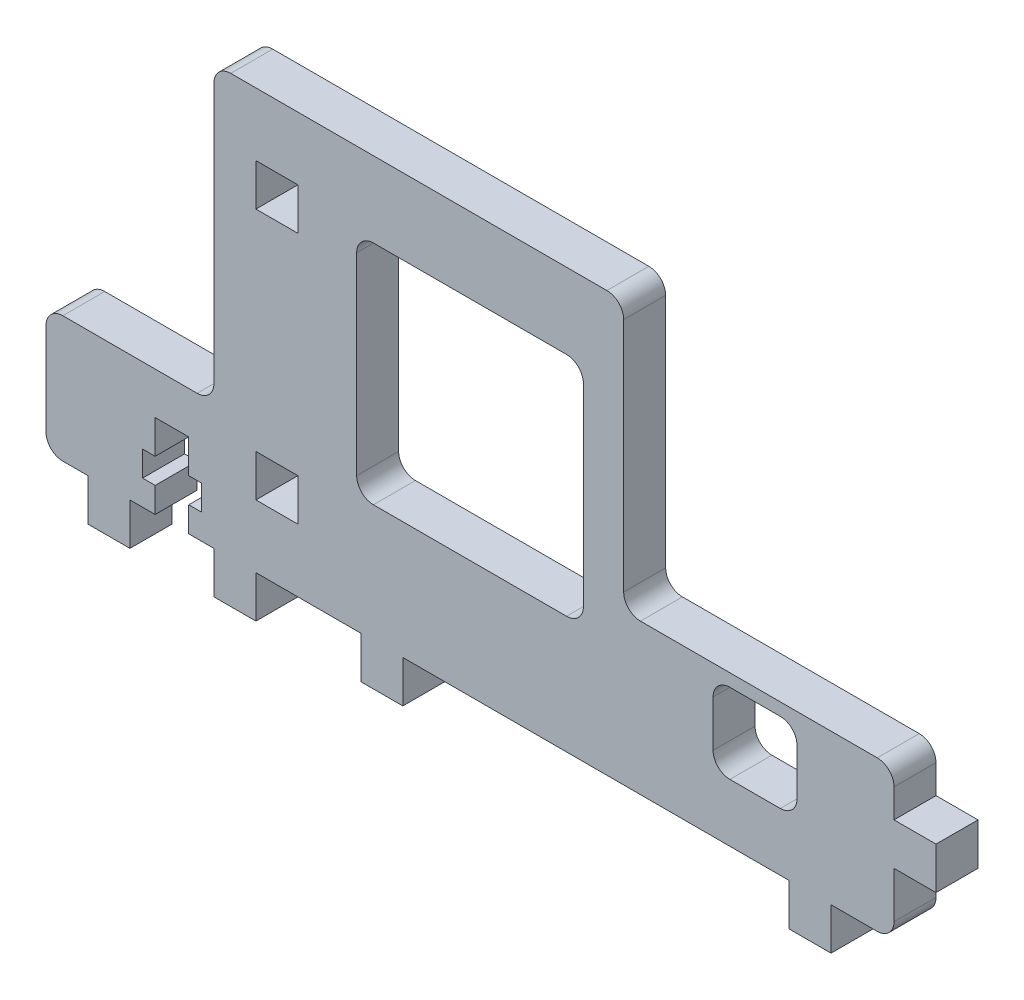
SolidWorks part; units mm, degrees
ref_plane "Plan de face" through (0, 0, 0) normal (0, 0, 1) x (1, 0, 0)
ref_plane "Plan de dessus" through (0, 0, 0) normal (0, 1, 0) x (1, 0, 0)
ref_plane "Plan de droite" through (0, 0, 0) normal (1, 0, 0) x (0, 0, -1)
sketch "Esquisse1" plane through (0, 0, 0) normal (0, 0, 1) x (1, 0, 0)
  line L1 (0, 0) -> (7.5, 0)
  line L3 (-10, 50) -> (38.8, 50)
  line L4 (71, 0) -> (71, 7.5)
  line L6 (38.8, 50) -> (38.8, 17.9)
  line L7 (38.8, 17.9) -> (71, 17.9)
  line L9 (7, 41) -> (34, 41)
  line L10 (7, 41) -> (7, 14)
  line L11 (7, 14) -> (34, 14)
  line L12 (34, 41) -> (34, 14)
  line L14 (0, 42.5) -> (-5, 42.5)
  line L16 (0, 37.5) -> (-5, 37.5)
  line L17 (-5, 42.5) -> (-5, 37.5)
  line L18 (0, 12.5) -> (-5, 12.5)
  line L20 (0, 7.5) -> (-5, 7.5)
  line L21 (-5, 12.5) -> (-5, 7.5)
  line L22 (71, 12.5) -> (76, 12.5)
  line L24 (71, 7.5) -> (76, 7.5)
  line L25 (76, 12.5) -> (76, 7.5)
  line L27 (71, 12.5) -> (71, 17.9)
  line L28 (12.5, 0) -> (58.5, 0)
  line L30 (7.5, 0) -> (7.5, -5)
  line L31 (7.5, -5) -> (12.5, -5)
  line L32 (12.5, 0) -> (12.5, -5)
  line L34 (58.5, 0) -> (58.5, -5)
  line L35 (58.5, -5) -> (63.5, -5)
  line L36 (63.5, 0) -> (63.5, -5)
  line L37 (63.5, 0) -> (71, 0)
  line L38 (0, 7.5) -> (0, 12.5)
  line L39 (0, 37.5) -> (0, 42.5)
  line L40 (-10, 50) -> (-10, 15)
  line L41 (-10, 15) -> (-30, 15)
  line L42 (-30, 15) -> (-30, 0)
  line L44 (0, 0) -> (0, 7.5) construction
  line L45 (0, 37.5) -> (0, 12.5) construction
  line L46 (-5, 0) -> (0, 0)
  line L47 (-30, 0) -> (-25, 0)
  line L67 (-25, 0) -> (-25, -5)
  line L68 (-25, -5) -> (-20, -5)
  line L69 (-20, -5) -> (-20, 0)
  line L70 (-20, 0) -> (-17, 0)
  line L71 (-17, 0) -> (-17, 3)
  line L72 (-17, 3) -> (-18.5, 3)
  line L73 (-18.5, 3) -> (-18.5, 6)
  line L74 (-18.5, 6) -> (-17, 6)
  line L75 (-17, 6) -> (-17, 10)
  line L76 (-17, 10) -> (-13, 10)
  line L77 (-13, 10) -> (-13, 6)
  line L78 (-13, 6) -> (-11.5, 6)
  line L79 (-11.5, 6) -> (-11.5, 3)
  line L80 (-11.5, 3) -> (-13, 3)
  line L81 (-13, 3) -> (-13, 0)
  line L82 (-13, 0) -> (-10, 0)
  line L83 (-10, 0) -> (-10, -5)
  line L84 (-10, -5) -> (-5, -5)
  line L85 (-5, -5) -> (-5, 0)
  line L87 (51.45, 14.9) -> (57.45, 14.9) construction
  line L88 (51.45, 14.9) -> (51.45, 8.9) construction
  line L89 (51.45, 8.9) -> (57.45, 8.9) construction
  line L90 (57.45, 14.9) -> (57.45, 8.9) construction
  line L91 (49.45, 16.4) -> (59.45, 16.4)
  line L92 (49.45, 16.4) -> (49.45, 6.9)
  line L93 (49.45, 6.9) -> (59.45, 6.9)
  line L94 (59.45, 16.4) -> (59.45, 6.9)
  line B0 (-15, 0) -> (-15, 11.2208) construction
  dimension "D1" = 71
  dimension "D2" = 32.2
  dimension "D3" = 27
  dimension "D4" = 27
  dimension "D5" = 50
  dimension "D6" = 14
  dimension "D7" = 17.9
  dimension "D8" = 4.8
  dimension "D9" = 5
  dimension "D10" = 7.5
  dimension "D11" = 7.5
  dimension "D12" = 7.5
  dimension "D13" = 5
  dimension "D14" = 7.5
  dimension "D15" = 5
  dimension "D16" = 15
  dimension "D17" = 20
  dimension "D18" = 5
  dimension "D19" = 6.5
  dimension "D20" = 3
  dimension "D21" = 6
  dimension "D22" = 13.55
  dimension "D23" = 2
  dimension "D24" = 2
  dimension "D25" = 2
  dimension "D26" = 1.5
sketch_block_instance "Insert M4 plots ep 5mm-7"
sketch_block "Insert M4 plots ep 5mm" parameters "D1"=10, "D2"=5, "D3"=5, "D4"=7, "D5"=4, "D6"=3, "D7"=3, "D8"=10
extrude "Boss.-Extru.1" add sketch "Esquisse1" along normal blind 5
fillet "Congé1" radius 2 16 edges at (34, 41, 2.5) (34, 14, 2.5) (7, 41, 2.5) (7, 14, 2.5) (38.8, 17.9, 2.5) (71, 17.9, 2.5) (38.8, 50, 2.5) (71, 0, 2.5) (-30, 15, 2.5) (-10, 15, 2.5) (-10, 50, 2.5) (-30, 0, 2.5) (59.45, 16.4, 2.5) (49.45, 16.4, 2.5) (59.45, 6.9, 2.5) (49.45, 6.9, 2.5)
